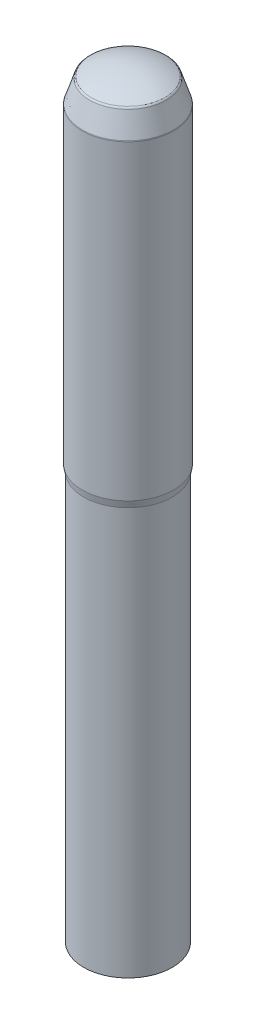
SolidWorks part; units mm, degrees
ref_plane "Plano frontal" through (0, 0, 0) normal (0, 0, 1) x (1, 0, 0)
ref_plane "Plano superior" through (0, 0, 0) normal (0, 1, 0) x (1, 0, 0)
ref_plane "Plano direito" through (0, 0, 0) normal (1, 0, 0) x (0, 0, -1)
sketch "Esboço2" plane through (0, 0, 0) normal (0, 0, 1) x (1, 0, 0)
  line L0 (0, 0) -> (0, 29.3)
  line L1 (0, 29.3) -> (-0.1, 29.8)
  line L2 (-0.1, 29.8) -> (-0.1, 52.1683)
  line L3 (3.185, 54.56) -> (3.185, 0) construction
  line L4 (-0.0902, 52.2302) -> (0.4278, 53.8229)
  line L5 (0, 0) -> (3.185, 0)
  line L6 (3.185, 54.56) -> (3.185, 0)
  arc A0 (3.185, 54.56) -> (0.5295, 53.9404) centre (3.185, 48.56) ccw
  arc A1 (-0.1, 52.1683) -> (-0.0902, 52.2302) centre (0.1, 52.1683) cw
  arc A2 (0.4278, 53.8229) -> (0.5295, 53.9404) centre (0.618, 53.761) cw
  point P11 (-0.1, 52.2)
  point P14 (0.4536, 53.9022)
  dimension "D3" = 12
  dimension "D9" = 0.2
  dimension "D1" = 6.57
  dimension "D2" = 29.3
  dimension "D4" = 25.26
  dimension "D5" = 6.37
  dimension "D6" = 22.4
  dimension "D7" = 1.79
  dimension "D8" = 0.5
revolve "Revolução1" add sketch "Esboço2" angle 360 about L3
sketch "Esboço3" plane through (0, 0, 0) normal (0, 0, 1) x (1, 0, 0)
  line L0 (-4.8667, 16.1497) -> (-0.8013, 16.2207)
  line L1 (-4.8758, 12.2257) -> (-5.4498, 15.4408)
  line L2 (-2.8584, 10.1263) -> (-4.5584, 11.6551)
  line L3 (-2.5268, 9.4316) -> (-2.0493, 0.3213)
  line L4 (-1.8281, -0.0807) -> (-0.717, -0.0807)
  line L5 (-1.8281, -0.0807) -> (-1.8281, 0.3213)
  line L6 (0.0722, 25.3197) -> (0, 0) construction
  line L7 (-0.8013, 16.2207) -> (0.0463, 16.2207)
  arc A0 (-4.8667, 16.1497) -> (-5.4498, 15.4408) centre (-4.8562, 15.5468) ccw
  arc A1 (-4.8758, 12.2257) -> (-4.5584, 11.6551) centre (-3.8864, 12.4024) ccw
  arc A2 (-2.5268, 9.4316) -> (-2.8584, 10.1263) centre (-3.5304, 9.379) ccw
